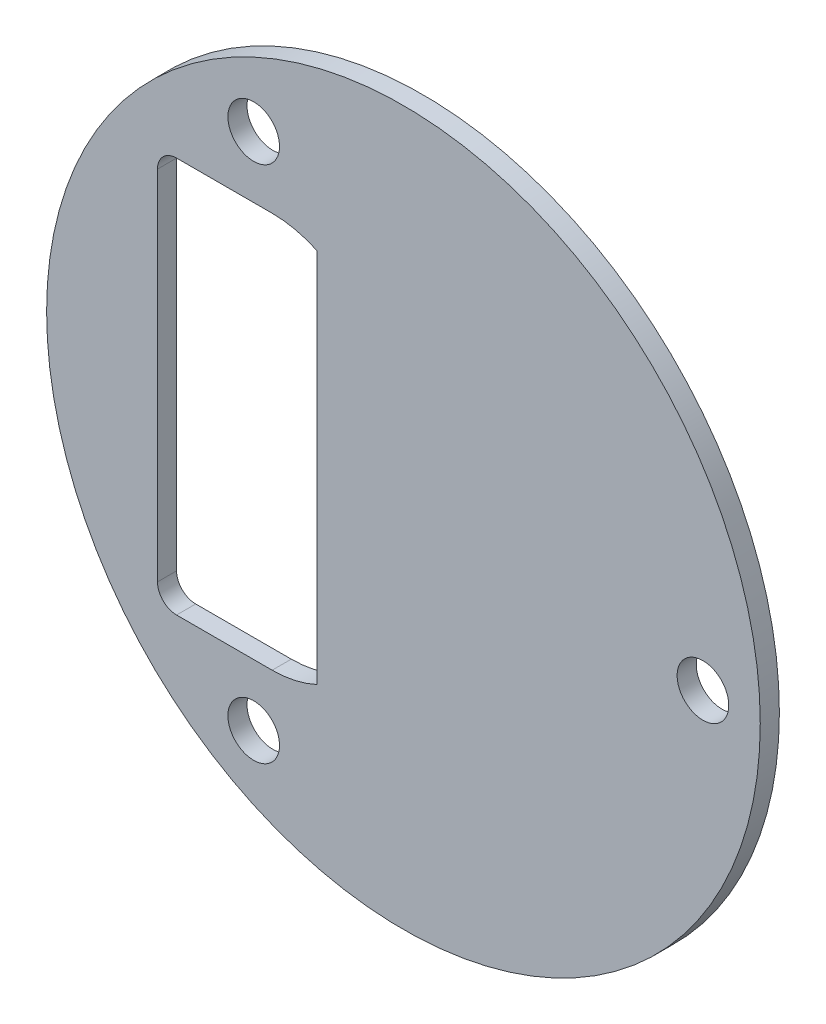
SolidWorks part; units mm, degrees
material "Balsa"
ref_plane "Ebene vorne" through (0, 0, 0) normal (0, 0, 1) x (1, 0, 0)
ref_plane "Ebene oben" through (0, 0, 0) normal (0, 1, 0) x (1, 0, 0)
ref_plane "Ebene rechts" through (0, 0, 0) normal (1, 0, 0) x (0, 0, -1)
sketch "Sketch1" plane through (0, 0, 0) normal (0, 0, 1) x (1, 0, 0)
  line L0 (0, 0) -> (47, 0) construction
  line L1 (-46.6036, -31.05) -> (-35.6036, -31.05) construction
  line L2 (-35.6036, -31.05) -> (-20.6036, -31.05)
  line L3 (-20.6036, -31.05) -> (-13.6036, -31.05) construction
  line L4 (-13.6036, 29.5) -> (-13.6036, -29.5)
  line L5 (-13.6036, 31.05) -> (-20.6036, 31.05) construction
  line L6 (-20.6036, 31.05) -> (-20.6036, -31.05) construction
  line L7 (-20.6036, 31.05) -> (-35.6036, 31.05)
  line L8 (-35.6036, 31.05) -> (-35.6036, -31.05)
  line L9 (-38.6036, 28.05) -> (-38.6036, 2.45)
  line L10 (-46.6036, -31.05) -> (-46.6036, 2.45) construction
  line L11 (-46.6036, 2.45) -> (-38.6036, 2.45) construction
  line L12 (-38.6036, 2.45) -> (-38.6036, -28.05)
  line L13 (-13.6036, 31.05) -> (-13.6036, 29.5) construction
  line L14 (-13.6036, -29.5) -> (-13.6036, -31.05) construction
  line L16 (-13.6036, 0) -> (0, 0) construction
  circle A0 centre (0, 0) radius 56
  circle A1 centre (47, 0) radius 4.05
  circle A2 centre (-23.5, -40.7032) radius 4.05
  circle A3 centre (-23.5, 40.7032) radius 4.05
  arc A4 (-35.6036, 31.05) -> (-38.6036, 28.05) centre (-35.6036, 28.05) ccw
  arc A5 (-38.6036, -28.05) -> (-35.6036, -31.05) centre (-35.6036, -28.05) ccw
  arc A6 (-20.6036, -31.05) -> (-13.6036, -29.5) centre (-20.6036, -14.4685) ccw
  arc A7 (-20.6036, 31.05) -> (-13.6036, 29.5) centre (-20.6036, 14.4685) cw
  point P11 (0, 0)
  dimension "D1" = 112
  dimension "D2" = 8.1
  dimension "D7" = 3
  dimension "D8" = 18
  dimension "D3" = 47
  dimension "D5" = 59
  dimension "D6" = 62.1
  dimension "D9" = 8
  dimension "D10" = 25
  dimension "D11" = 33.5
  dimension "D4" = 3
extrude "Boss-Extrude1" add sketch "Sketch1" along normal blind 3 contours A0 A3 A2 A1 L7 A7 L4 A6 L2 A5 L12 L9 A4
